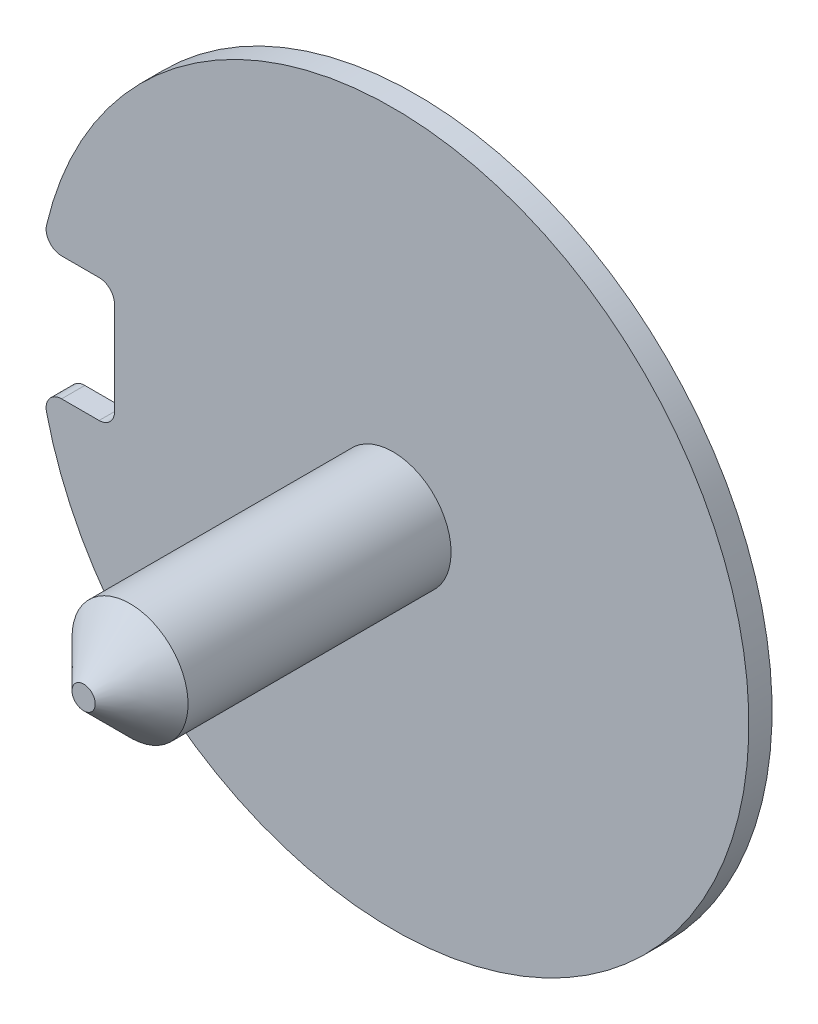
SolidWorks part; units mm, degrees
material "ABS"
ref_plane "Front Plane" through (0, 0, 0) normal (0, 0, 1) x (1, 0, 0)
ref_plane "Top Plane" through (0, 0, 0) normal (0, 1, 0) x (1, 0, 0)
ref_plane "Right Plane" through (0, 0, 0) normal (1, 0, 0) x (0, 0, -1)
sketch "Sketch1" plane through (0, 0, 0) normal (0, 0, 1) x (1, 0, 0)
  circle A0 centre (0, 8) radius 46
  dimension "D1" = 92
extrude "Boss-Extrude1" add sketch "Sketch1" along normal blind 3
sketch "Sketch3" plane through (0, 0, 0) normal (0, 0, -1) x (-1, 0, 0)
  line L0 (-14, 8) -> (14, 8) construction
  circle A2 centre (0, 8) radius 14 construction
  circle A3 centre (0, 0) radius 3.05
  circle A4 centre (0, 16) radius 3.05
  dimension "D1" = 28
  dimension "D2" = 6.1
extrude "Cut-Extrude2" cut sketch "Sketch3" against normal blind 1.1
sketch "Sketch2" plane through (0, 0, 0) normal (0, 0, -1) x (-1, 0, 0)
  line L0 (0, 22) -> (0, -6) construction
  line L1 (-14, 8) -> (14, 8) construction
  line L2 (-9, 9.05) -> (-9, 6.95) construction
  line L3 (-7.95, 9.05) -> (-7.95, 6.95)
  line L4 (-10.05, 9.05) -> (-10.05, 6.95)
  line L5 (9, 9.05) -> (9, 6.95) construction
  line L6 (7.95, 9.05) -> (7.95, 6.95)
  line L7 (10.05, 9.05) -> (10.05, 6.95)
  circle A0 centre (0, 8) radius 14 construction
  arc A1 (-7.95, 9.05) -> (-10.05, 9.05) centre (-9, 9.05) ccw
  arc A2 (-10.05, 6.95) -> (-7.95, 6.95) centre (-9, 6.95) ccw
  arc A3 (7.95, 9.05) -> (10.05, 9.05) centre (9, 9.05) cw
  arc A4 (10.05, 6.95) -> (7.95, 6.95) centre (9, 6.95) cw
  point P9 (-9, 8)
  point P17 (9, 8)
  dimension "D1" = 28
  dimension "D2" = 2.1
  dimension "D3" = 2.1
  dimension "D4" = 5
extrude "Cut-Extrude1" cut sketch "Sketch2" against normal blind 2.2
sketch "Sketch4" plane through (0, 0, 3) normal (0, 0, 1) x (1, 0, 0)
  circle A0 centre (0, 8) radius 7.5
  dimension "D1" = 15
extrude "Boss-Extrude2" add sketch "Sketch4" along normal blind 40
chamfer "Chamfer1" distance 6 angle 45 1 edges at (7.5, 8, 43)
sketch "Sketch5" plane through (0, 0, 0) normal (0, 0, -1) x (-1, 0, 0)
  line L0 (-46, 8) -> (46, 8) construction
  line L4 (36, 16) -> (46, 16)
  line L5 (36, 16) -> (36, 0)
  line L6 (36, 0) -> (46, 0)
  line L7 (46, 16) -> (46, 0)
  line L8 (36, 16) -> (46, 0) construction
  line L9 (36, 0) -> (46, 16) construction
  circle A0 centre (0, 8) radius 46 construction
  point P5 (41, 8)
  point P10 (46, 8)
  dimension "D1" = 10
  dimension "D2" = 16
extrude "Size-Medicine" cut sketch "Sketch5" against normal up to next
fillet "Fillet1" radius 2 4 edges at (-36, 16, 1.5) (-36, 0, 1.5) (-45.299, 0, 1.5) (-45.299, 16, 1.5)
